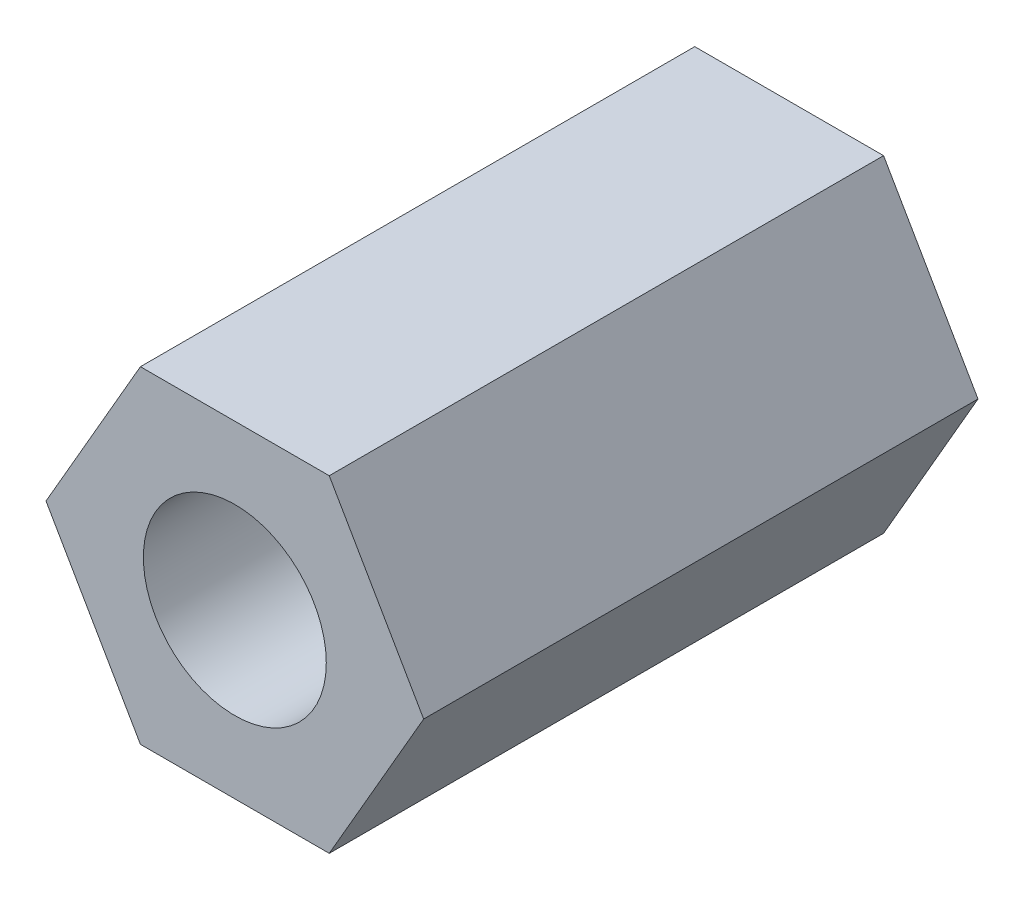
SolidWorks part; units mm, degrees
material "黄铜"
ref_plane "前视基准面" through (0, 0, 0) normal (0, 0, 1) x (1, 0, 0)
ref_plane "上视基准面" through (0, 0, 0) normal (0, 1, 0) x (1, 0, 0)
ref_plane "右视基准面" through (0, 0, 0) normal (1, 0, 0) x (0, 0, -1)
sketch "草图1" plane through (0, 0, 0) normal (0, 0, 1) x (1, 0, 0)
  line L1 (1.7032, 2.95) -> (-1.7032, 2.95)
  line L2 (-1.7032, 2.95) -> (-3.4064, 0)
  line L3 (-3.4064, 0) -> (-1.7032, -2.95)
  line L4 (-1.7032, -2.95) -> (1.7032, -2.95)
  line L5 (1.7032, -2.95) -> (3.4064, 0)
  line L6 (3.4064, 0) -> (1.7032, 2.95)
  circle A0 centre (0, 0) radius 2.95 construction
  dimension "D1" = 5.9
extrude "凸台-拉伸1" add sketch "草图1" along normal blind 10
hole_wizard "M4 螺纹孔1" positions "草图2" profile "草图3" tap size "M4" standard "GB" end condition through all
sketch "草图2" plane through (0, 0, 10) normal (0, 0, 1) x (1, 0, 0)
  point P0 (0, 0)
sketch "草图3" plane through (0, 0, 10) normal (1, 0, 0) x (0, -1, 0)
  line L0 (0, 0) -> (0, 10)
  line L1 (0, 10) -> (1.65, 10)
  line L2 (1.65, 10) -> (1.65, 0)
  line L5 (1.65, 0) -> (0, 0)
  line L11 (0, -6.35) -> (0, 107.95) construction
  dimension "通孔螺纹孔钻头直径" = 3.3
  dimension "通孔螺纹孔钻头深度" = 10
cosmetic thread "孔螺蚊线1"
